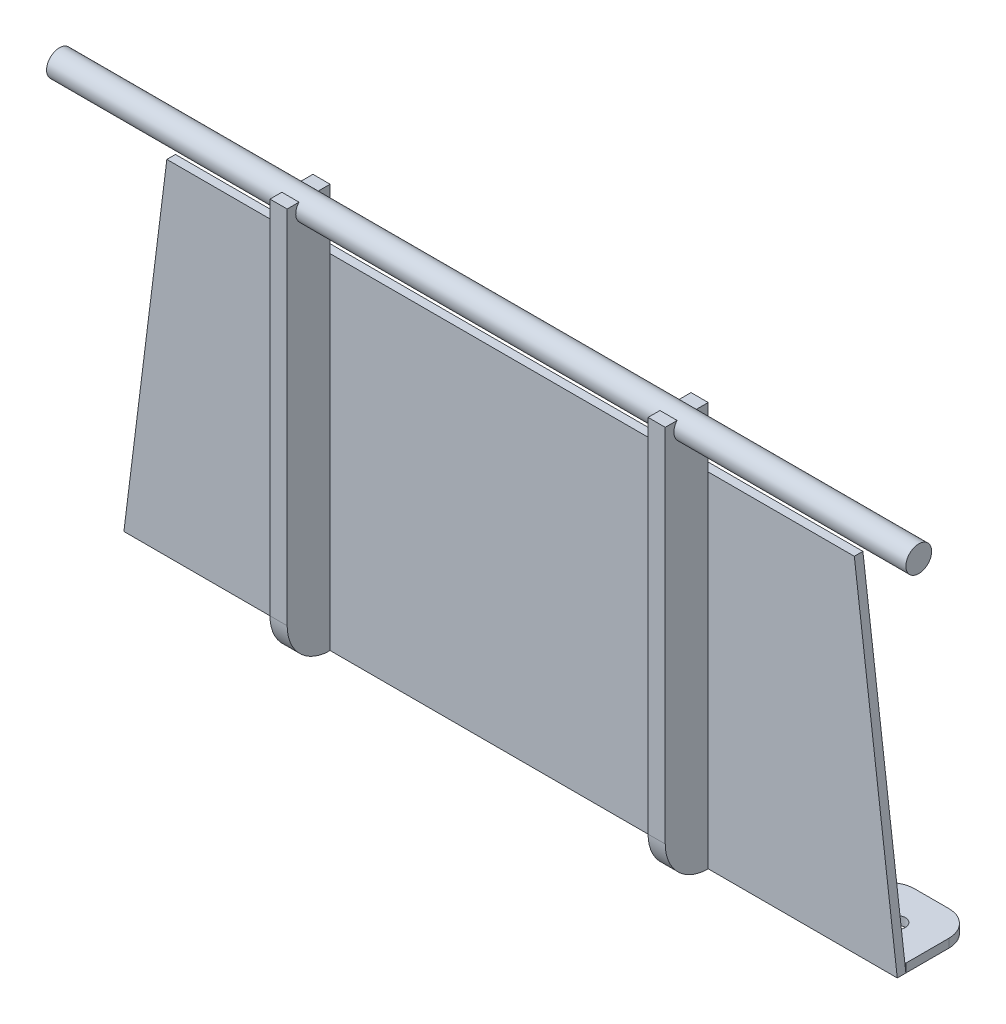
SolidWorks part; units mm, degrees
ref_plane "Front Plane" through (0, 0, 0) normal (0, 0, 1) x (1, 0, 0)
ref_plane "Top Plane" through (0, 0, 0) normal (0, 1, 0) x (1, 0, 0)
ref_plane "Right Plane" through (0, 0, 0) normal (1, 0, 0) x (0, 0, -1)
sketch "Sketch1" plane through (0, 0, 0) normal (0, 0, 1) x (1, 0, 0)
  line L0 (-45, 0) -> (45, 0)
  line L1 (45, 0) -> (45, 40) construction
  line L2 (45, 40) -> (40, 40) construction
  line L3 (40, 40) -> (-40, 40)
  line L4 (0, 40) -> (0, 0) construction
  line L5 (40, 40) -> (45, 0)
  line L6 (-40, 40) -> (-45, 0)
  point P2 (0, 0)
  dimension "D1" = 40
  dimension "D2" = 90
  dimension "D4" = 40
extrude "Boss-Extrude2" add sketch "Sketch1" along normal blind 1
ref_plane "Plane1" through (21, 0, 0) normal (1, 0, 0) x (0, 0, -1)
sketch "Sketch2" plane through (21, 0, 0) normal (1, 0, 0) x (0, 0, -1)
  line L2 (-1, 47) -> (-6, 47)
  line L5 (-1, 47) -> (-1, 0)
  line L6 (-1, 0) -> (-6, 0)
  line L7 (-6, 0) -> (-6, 47)
  point P2 (0, 0)
  point P6 (-1, 0)
  dimension "D1" = 5
  dimension "D2" = 47
extrude "Boss-Extrude3" add sketch "Sketch2" along normal blind 2
fillet "Fillet2" radius 5 1 edges at (22, 0, 6)
mirror "Mirror2" about plane through (0, 0, 0) normal (1, 0, 0) of "Fillet2", "Boss-Extrude3"
ref_plane "Plane2" through (0, 46, 0) normal (0, 1, 0) x (1, 0, 0)
ref_plane "Plane3" through (50, 0, 0) normal (1, 0, 0) x (0, 0, -1)
sketch "Sketch3" plane through (50, 0, 0) normal (1, 0, 0) x (0, 0, -1)
  line L0 (-1, 47) -> (-6, 47) construction
  line L1 (-1, 47) -> (-6, 47) construction
  line L2 (3.3, 46) -> (-3.3, 46) construction
  circle A0 centre (-3.5, 46) radius 1.5
  point P2 (-3.5, 46)
  point P6 (-3.5, 47)
  dimension "D1" = 3
extrude "Boss-Extrude5" add sketch "Sketch3" against normal blind 100 contours A0
sketch "Sketch5" plane through (0, 0, 0) normal (0, 1, 0) x (1, 0, 0)
  line L0 (-45, 0) -> (-45, 8)
  line L1 (-45, 8) -> (-35, 8)
  line L2 (-35, 8) -> (-35, 0)
  line L3 (-45, 0) -> (45, 0) construction
  line L4 (-35, 0) -> (-45, 0)
  dimension "D1" = 8
  dimension "D2" = 10
extrude "Boss-Extrude6" add sketch "Sketch5" along normal blind 1
fillet "Fillet3" radius 3 2 edges at (-35, 0.5, -8) (-45, 0.5, -8)
sketch "Sketch6" plane through (0, 1, 0) normal (0, 1, 0) x (1, 0, 0)
  line L0 (-44.875, 0) -> (-35.8787, 7.1213) construction
  arc A0 (-35, 5) -> (-38, 8) centre (-38, 5) ccw construction
  circle A1 centre (-40.3768, 3.5607) radius 1
  point P8 (0, 0)
  point P9 (-40.3768, 3.5607)
  dimension "D1" = 2
extrude "Cut-Extrude1" cut sketch "Sketch6" against normal blind 1
mirror "Mirror4" about plane through (0, 0, 0) normal (1, 0, 0) of "Fillet3", "Cut-Extrude1", "Boss-Extrude6"
